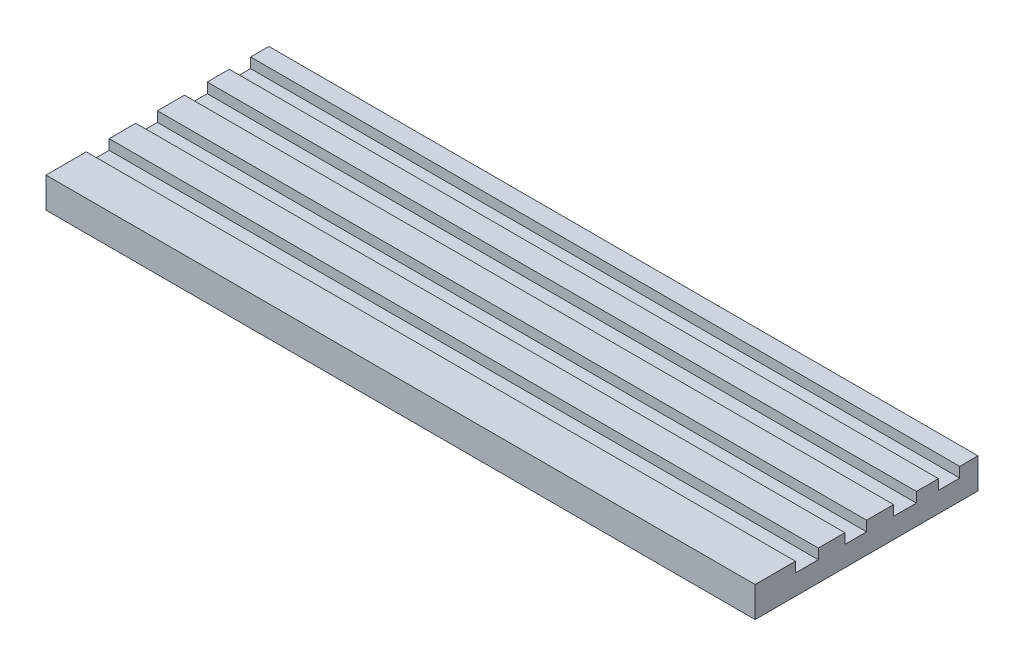
SolidWorks part; units mm, degrees
material "Alumina"
ref_plane "Front Plane" through (0, 0, 0) normal (0, 0, 1) x (1, 0, 0)
ref_plane "Top Plane" through (0, 0, 0) normal (0, 1, 0) x (1, 0, 0)
ref_plane "Right Plane" through (0, 0, 0) normal (1, 0, 0) x (0, 0, -1)
sketch "Sketch2" plane through (0, 0, 0) normal (0, 1, 0) x (1, 0, 0)
  line L1 (0, 0) -> (70, 0)
  line L2 (0, 0) -> (0, 22)
  line L3 (0, 22) -> (70, 22)
  line L4 (70, 0) -> (70, 22)
  dimension "D1" = 70
  dimension "D2" = 22
extrude "Boss-Extrude1" add sketch "Sketch2" along normal blind 3
sketch "Sketch3" plane through (0, 3, 0) normal (0, 1, 0) x (1, 0, 0)
  line L0 (0, 22) -> (0, 0) construction
  line L1 (0, 20.1975) -> (70, 20.1975)
  line L2 (0, 20.1975) -> (0, 18.0952)
  line L3 (0, 18.0952) -> (70, 18.0952)
  line L4 (70, 20.1975) -> (70, 18.0952)
  line L5 (70, 0) -> (70, 22) construction
  line L7 (0, 15.9179) -> (70, 15.9179)
  line L8 (0, 15.9179) -> (0, 13.6654)
  line L9 (0, 13.6654) -> (70, 13.6654)
  line L10 (70, 15.9179) -> (70, 13.6654)
  line L11 (0, 11) -> (70, 11)
  line L12 (0, 11) -> (0, 8.8602)
  line L13 (0, 8.8602) -> (70, 8.8602)
  line L14 (70, 11) -> (70, 8.8602)
  line L15 (0, 6.2323) -> (70, 6.2323)
  line L16 (0, 6.2323) -> (0, 3.9798)
  line L17 (0, 3.9798) -> (70, 3.9798)
  line L18 (70, 6.2323) -> (70, 3.9798)
extrude "Cut-Extrude1" cut sketch "Sketch3" against normal blind 1
